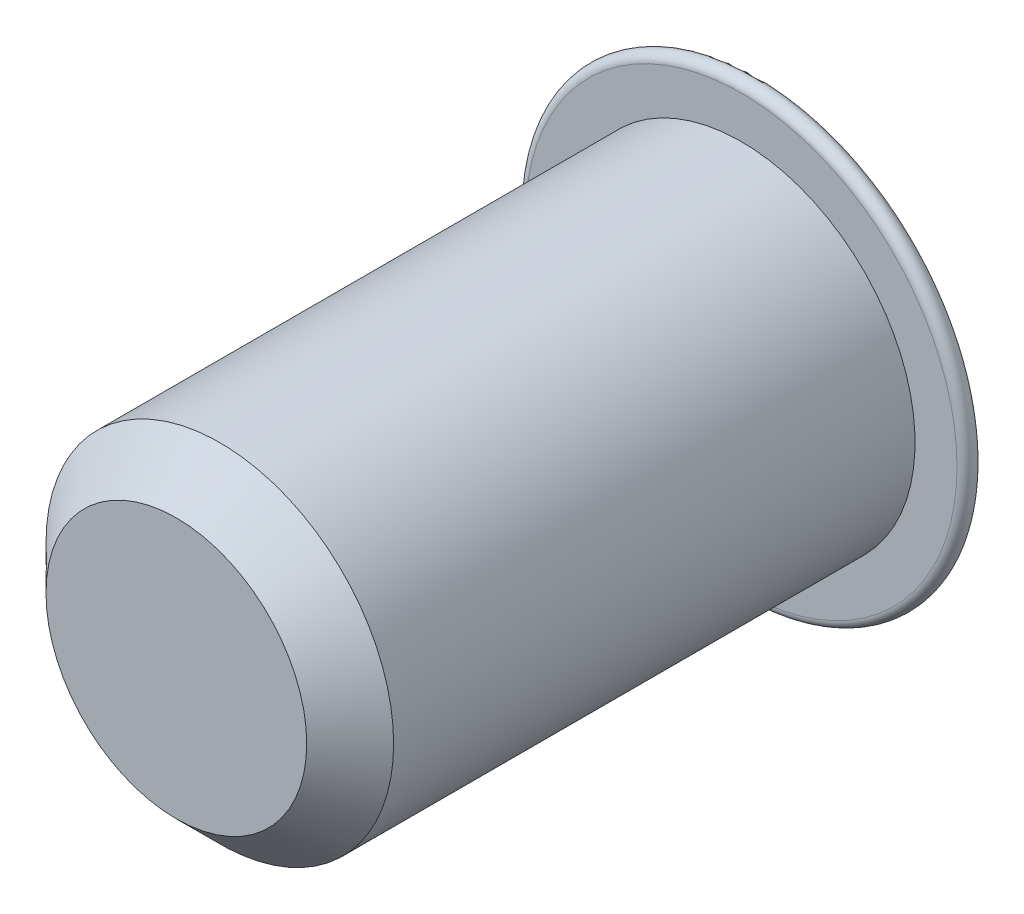
SolidWorks part; units mm, degrees
ref_plane "Plan de face" through (0, 0, 0) normal (0, 0, 1) x (1, 0, 0)
ref_plane "Plan de dessus" through (0, 0, 0) normal (0, 1, 0) x (1, 0, 0)
ref_plane "Plan de droite" through (0, 0, 0) normal (1, 0, 0) x (0, 0, -1)
sketch "Esquisse1" plane through (0, 0, 0) normal (0, 1, 0) x (1, 0, 0)
  line L0 (0, 0) -> (0, 6.5)
  line L1 (0, 6.5) -> (-1, 6.5)
  line L2 (-1, 6.5) -> (0, 7) construction
  line L3 (0, 7) -> (2, 7) construction
  line L4 (2, 7) -> (2, 0)
  line L5 (2, 0) -> (0, 0)
  spline S0 degree 2 poles (-1, 6.5) (0, 7) (2, 7) knots 0 0 0 1 1 1
  dimension "D1" = 7
  dimension "D2" = 1
  dimension "D3" = 0.5
  dimension "D4" = 2
revolve "Révolution1" add sketch "Esquisse1" angle 360 about L4
fillet "Congé1" radius 0.1 1 edges at (-1, 0, -6.5)
chamfer "Chanfrein1" distance 0.5 angle 45 1 edges at (0, 0, 0)
sketch "Esquisse3" plane through (0, 0, -6.5) normal (0, 0, 1) x (1, 0, 0)
  line L0 (2, 0) -> (-0.1659, -1.2138) construction
  circle A0 centre (2, 0) radius 2.4829 construction
ref_plane "Plan1" through (0.478, -0.853, 0) normal (-0.4889, 0.8723, 0) x (-0.8723, -0.4889, 0)
sketch "Esquisse4" plane through (0.478, -0.853, 0) normal (-0.4889, 0.8723, 0) x (-0.8723, -0.4889, 0)
  line L0 (-1.7447, -6.6952) -> (-1.7447, -7.9071) construction
  line L1 (-4.2581, -6.6952) -> (0.7687, -6.6952) construction
  line L3 (-2.0321, -8.1324) -> (-1.4573, -8.1324)
  line L4 (-2.0321, -8.1324) -> (-2.0321, -6.7804)
  line L5 (-2.0321, -6.7804) -> (-1.4573, -6.7804)
  line L6 (-1.4573, -8.1324) -> (-1.4573, -6.7804)
  line L7 (-2.0321, -8.1324) -> (-1.4573, -6.7804) construction
  line L8 (-2.0321, -6.7804) -> (-1.4573, -8.1324) construction
  point P4 (-1.7447, -7.4564)
extrude "Enlèv. mat.-Extru.1" cut sketch "Esquisse4" against normal mid plane 20
